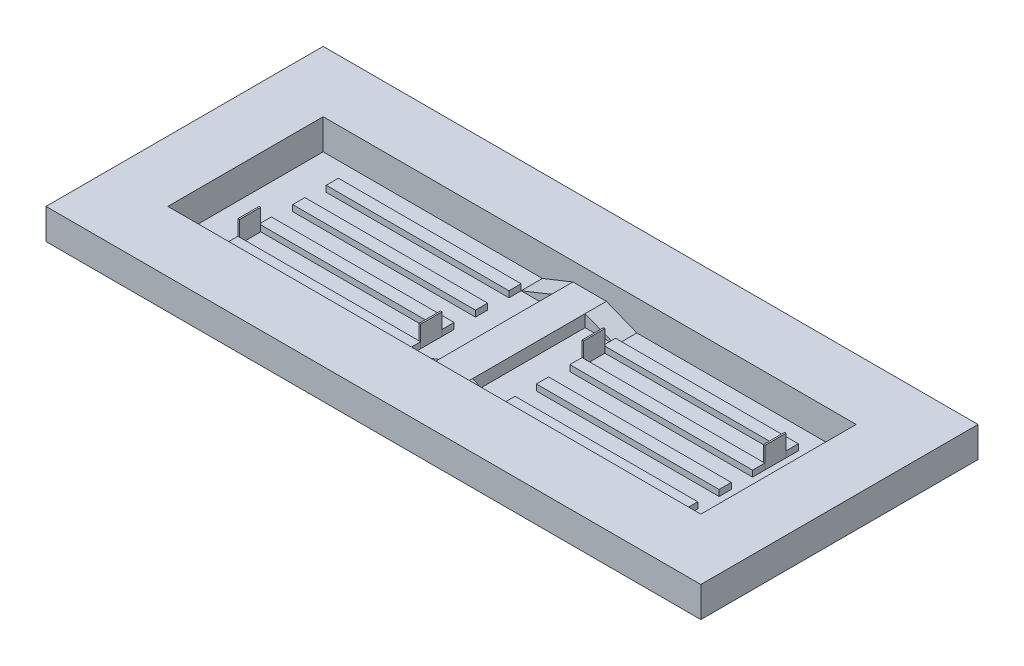
SolidWorks part; units mm, degrees
ref_plane "前基準面" through (0, 0, 0) normal (0, 0, 1) x (1, 0, 0)
ref_plane "上基準面" through (0, 0, 0) normal (0, 1, 0) x (1, 0, 0)
ref_plane "右基準面" through (0, 0, 0) normal (1, 0, 0) x (0, 0, -1)
sketch "草圖1" plane through (0, 0, 0) normal (0, 1, 0) x (1, 0, 0)
  line L1 (-10750, 4550) -> (10750, 4550)
  line L2 (-10750, 4550) -> (-10750, -4550)
  line L3 (-10750, -4550) -> (10750, -4550)
  line L4 (10750, 4550) -> (10750, -4550)
  line L5 (-10750, 4550) -> (10750, -4550) construction
  line L6 (-10750, -4550) -> (10750, 4550) construction
  point P0 (0, 0)
  dimension "D1" = 21500
  dimension "D2" = 9100
extrude "伸長1" add sketch "草圖1" along normal blind 1000
sketch "草圖2" plane through (0, 1000, 0) normal (0, 1, 0) x (1, 0, 0)
  line L12 (8750, -2550) -> (8750, 2550)
  line L13 (8750, 2550) -> (-8750, 2550)
  line L14 (-8750, 2550) -> (-8750, -2550)
  line L15 (-8750, -2550) -> (8750, -2550)
  line L16 (8750, -2550) -> (8750, 2550)
  line L17 (8750, 2550) -> (-8750, 2550)
  line L18 (-8750, 2550) -> (-8750, -2550)
  line L19 (-8750, -2550) -> (8750, -2550)
  dimension "D1" = 2000
extrude "伸長2" cut sketch "草圖2" against normal blind 999
sketch "草圖3" plane through (0, 1, 0) normal (0, 1, 0) x (1, 0, 0)
  line L0 (8750, 2550) -> (-8750, 2550) construction
  line L1 (-550, 2550) -> (550, 2550)
  line L2 (-550, 2550) -> (-550, -2550)
  line L3 (-550, -2550) -> (550, -2550)
  line L4 (550, 2550) -> (550, -2550)
  line L5 (-550, 2550) -> (550, -2550) construction
  line L6 (-550, -2550) -> (550, 2550) construction
  point P0 (0, 0)
  dimension "D1" = 1100
extrude "伸長3" add sketch "草圖3" along normal blind 400
sketch "草圖5" plane through (0, 0, -2550) normal (0, 0, 1) x (1, 0, 0)
  line L0 (550, 401) -> (1550, 1)
  line L1 (8750, 1) -> (550, 1) construction
  line L2 (1550, 1) -> (550, 1)
  line L3 (550, 1) -> (550, 401)
  line L4 (-550, 1) -> (-550, 401)
  line L5 (-550, 401) -> (-1550, 1)
  line L6 (-550, 1) -> (-8750, 1) construction
  line L7 (-1550, 1) -> (-550, 1)
  dimension "D1" = 1000
  dimension "D2" = 1000
extrude "伸長4" add sketch "草圖5" along normal blind 700
sketch "草圖6" plane through (0, 0, 2550) normal (0, 0, -1) x (-1, 0, 0)
  line L0 (-550, 1) -> (-550, 401)
  line L1 (-550, 401) -> (-1550, 1)
  line L2 (-550, 1) -> (-8750, 1) construction
  line L3 (-1550, 1) -> (-550, 1)
  line L4 (550, 1) -> (550, 401)
  line L5 (550, 401) -> (1550, 1)
  line L6 (8750, 1) -> (550, 1) construction
  line L7 (1550, 1) -> (550, 1)
  dimension "D1" = 1000
  dimension "D2" = 1000
extrude "伸長5" add sketch "草圖6" along normal blind 700
sketch "草圖7" plane through (0, 1, 0) normal (0, 1, 0) x (1, 0, 0)
  line L0 (1550, 1850) -> (1550, -1850) construction
  line L1 (1550, -1850) -> (7550, -1850) construction
  line L2 (7550, -1850) -> (7550, 1850) construction
  line L3 (7550, 1850) -> (1550, 1850) construction
  line L4 (8750, -2550) -> (8750, 2550) construction
  line L5 (1550, 1850) -> (1550, 2550) construction
  line L6 (4550, 1450) -> (4550, 750) construction
  line L7 (1550, 1850) -> (7550, 1850)
  line L8 (1550, 1850) -> (1550, 1450)
  line L9 (1550, 1450) -> (7550, 1450)
  line L10 (7550, 1850) -> (7550, 1450)
  line L11 (7550, -1850) -> (1550, -1850)
  line L12 (7550, -1850) -> (7550, -1450)
  line L13 (7550, -1450) -> (1550, -1450)
  line L14 (1550, -1850) -> (1550, -1450)
  line L15 (1550, 750) -> (7550, 750)
  line L16 (1550, 750) -> (1550, 350)
  line L17 (1550, 350) -> (7550, 350)
  line L18 (7550, 750) -> (7550, 350)
  line L19 (7550, -750) -> (1550, -750)
  line L20 (7550, -750) -> (7550, -350)
  line L21 (7550, -350) -> (1550, -350)
  line L22 (1550, -750) -> (1550, -350)
  line L23 (4550, 750) -> (4550, 350) construction
  line L24 (4550, 350) -> (4550, -350) construction
  line L25 (4550, -350) -> (4550, -750) construction
  line L26 (4550, -750) -> (4550, -1450) construction
  line L27 (4550, -1450) -> (4550, -1850) construction
  line L28 (4550, 1450) -> (4550, 1850) construction
  line L29 (4550, 1850) -> (4550, 2550) construction
  line L30 (8750, 2550) -> (1550, 2550) construction
  line L31 (4550, -1850) -> (4550, -2550) construction
  line L32 (1550, -2550) -> (8750, -2550) construction
  dimension "D1" = 1200
  dimension "D2" = 400
  dimension "D3" = 3000
extrude "伸長6" add sketch "草圖7" along normal blind 200
sketch "草圖8" plane through (0, 401, 0) normal (0, 1, 0) x (1, 0, 0)
  line L3 (550, 2550) -> (-550, 2550) construction
  line L4 (0, 2550) -> (0, -2550) construction
  line L5 (-550, -2550) -> (550, -2550) construction
ref_plane "平面1" through (0, 0, 0) normal (1, 0, 0) x (0, 0, -1)
mirror "鏡射1" about plane through (0, 0, 0) normal (1, 0, 0) of "伸長6"
sketch "草圖9" plane through (0, 1, 0) normal (0, 1, 0) x (1, 0, 0)
  line L0 (-1550, -750) -> (-7550, -750) construction
  line L1 (-7550, -1450) -> (-7500, -1450)
  line L2 (-7550, -1450) -> (-7550, -750)
  line L3 (-7550, -750) -> (-7500, -750)
  line L4 (-7500, -1450) -> (-7500, -750)
  line L5 (7550, 750) -> (1550, 750) construction
  line L6 (7550, 1450) -> (7500, 1450)
  line L7 (7550, 1450) -> (7550, 750)
  line L8 (7550, 750) -> (7500, 750)
  line L9 (7500, 1450) -> (7500, 750)
  line L10 (-7550, -1450) -> (-1550, -1450) construction
  line L11 (-1600, -1450) -> (-1550, -1450)
  line L12 (-1600, -1450) -> (-1600, -750)
  line L13 (-1600, -750) -> (-1550, -750)
  line L14 (-1550, -1450) -> (-1550, -750)
  line L16 (1550, 1450) -> (1600, 1450)
  line L17 (1550, 1450) -> (1550, 750)
  line L18 (1550, 750) -> (1600, 750)
  line L19 (1600, 1450) -> (1600, 750)
  dimension "D1" = 50
  dimension "D2" = 50
  dimension "D3" = 50
  dimension "D4" = 50
extrude "伸長7" add sketch "草圖9" along normal blind 700 separate body
